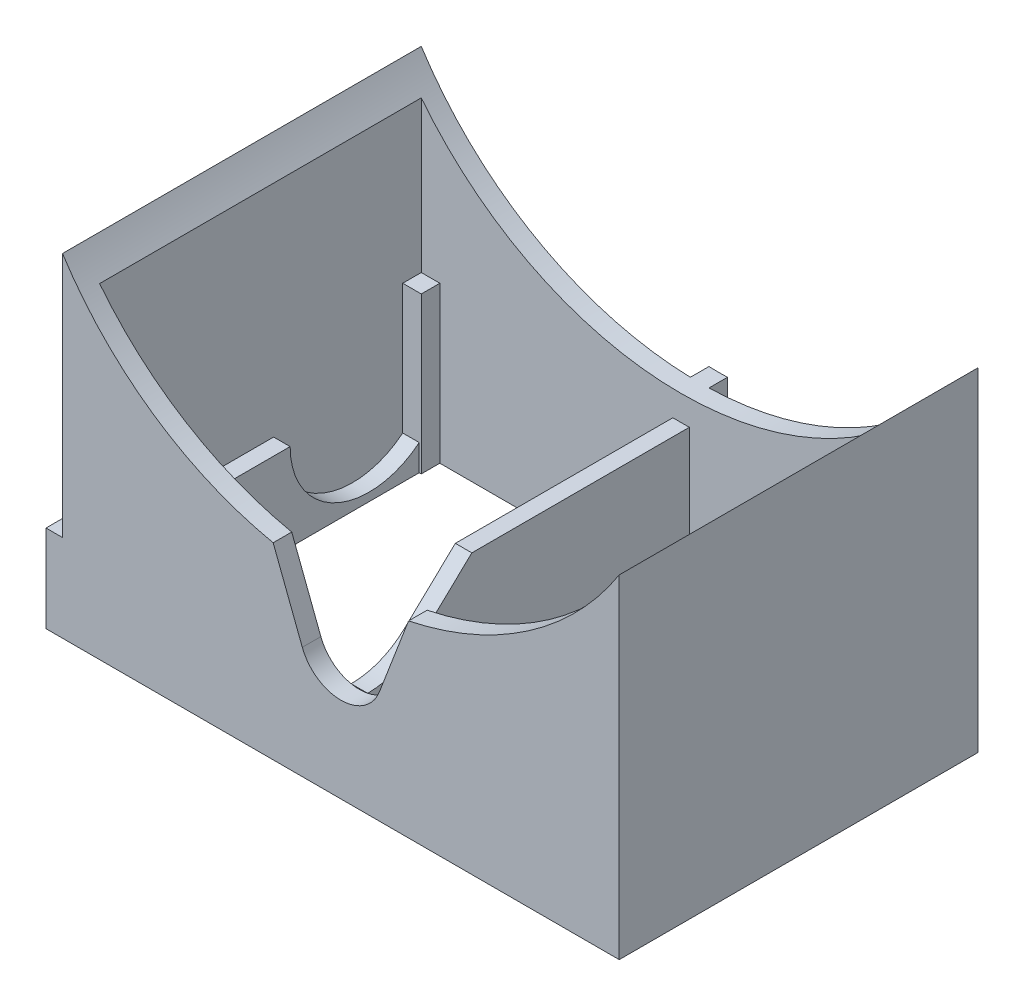
SolidWorks part; units mm, degrees
ref_plane "前视基准面" through (0, 0, 0) normal (0, 0, 1) x (1, 0, 0)
ref_plane "上视基准面" through (0, 0, 0) normal (0, 1, 0) x (1, 0, 0)
ref_plane "右视基准面" through (0, 0, 0) normal (1, 0, 0) x (0, 0, -1)
sketch "草图1" plane through (0, 0, 0) normal (0, 1, 0) x (1, 0, 0)
  line L0 (0, 0) -> (4.5, 0)
  line L1 (4.5, 0) -> (4.5, 4.5)
  line L2 (4.5, 4.5) -> (121.5, 4.5) construction
  line L3 (121.5, 4.5) -> (121.5, 0)
  line L4 (121.5, 0) -> (126, 0)
  line L5 (126, 0) -> (126, -69)
  line L6 (126, -69) -> (121.5, -69)
  line L7 (121.5, -69) -> (121.5, -73.5)
  line L8 (121.5, -73.5) -> (4.5, -73.5) construction
  line L9 (4.5, -73.5) -> (4.5, -69)
  line L10 (4.5, -69) -> (0, -69)
  line L11 (0, -69) -> (0, 0)
  line L12 (4.5, 4.5) -> (61, 4.5)
  line L13 (-4.5, 9) -> (130.5, 9)
  line L14 (-4.5, 9) -> (-4.5, -78)
  line L15 (-4.5, -78) -> (130.5, -78)
  line L16 (130.5, 9) -> (130.5, -78)
  line L17 (61, 4.5) -> (61, -73.5)
  line L18 (61, -73.5) -> (4.5, -73.5)
  line L19 (121.5, 4.5) -> (65, 4.5)
  line L20 (65, 4.5) -> (65, -73.5)
  line L21 (65, -73.5) -> (121.5, -73.5)
  line L22 (61, 4.5) -> (65, 4.5)
  point P17 (63, 4.5)
  point P18 (63, -73.5)
  point P23 (63, 4.5)
  dimension "D1" = 126
  dimension "D2" = 78
  dimension "D3" = 4.5
  dimension "D4" = 4.5
  dimension "D5" = 4.5
  dimension "D6" = 4.5
  dimension "D7" = 4.5
  dimension "D8" = 4.5
  dimension "D9" = 4.5
  dimension "D10" = 4.5
  dimension "D11" = 4
extrude "凸台-拉伸1" add sketch "草图1" along normal blind 37.8
sketch "草图2" plane through (0, 37.8, 0) normal (0, 1, 0) x (1, 0, 0)
  line L0 (4.5, 4.5) -> (61, 4.5) construction
  line L1 (-4.5, 9) -> (130.5, 9)
  line L2 (-4.5, 9) -> (-4.5, -78)
  line L3 (-4.5, -78) -> (130.5, -78)
  line L4 (130.5, 9) -> (130.5, -78)
  line L5 (0, 4.5) -> (126, 4.5)
  line L6 (0, 4.5) -> (0, -73.5)
  line L7 (0, -73.5) -> (126, -73.5)
  line L8 (126, 4.5) -> (126, -73.5)
  line L9 (0, -69) -> (0, 0) construction
  line L10 (61, -73.5) -> (4.5, -73.5) construction
  line L11 (126, 0) -> (126, -69) construction
extrude "凸台-拉伸2" add sketch "草图2" along normal blind 43
sketch "草图3" plane through (0, 0, 78) normal (0, 0, 1) x (1, 0, 0)
  line L0 (63, 80.8) -> (63, 167.3756) construction
  line L1 (-4.5, 80.8) -> (130.5, 80.8) construction
  line L2 (130.5, 80.8) -> (130.5, 0) construction
  line L3 (32.8626, 43.9) -> (91.0379, 43.9) construction
  line L4 (-4.5, 0) -> (130.5, 0) construction
  line L5 (-4.5, 80.8) -> (130.5, 80.8)
  arc A0 (-4.5, 80.8) -> (130.5, 80.8) centre (63, 124.0878) ccw
  dimension "D1" = 43.9
extrude "切除-拉伸1" cut sketch "草图3" against normal through all
sketch "草图4" plane through (0, 0, 78) normal (0, 0, 1) x (1, 0, 0)
  line L0 (63, 43.9) -> (63, 22.4366) construction
  line L1 (53.65, 27.1691) -> (46.585, 45.5981)
  line L2 (46.585, 45.5981) -> (79.415, 45.5981)
  line L3 (79.415, 45.5981) -> (72.35, 27.1691)
  line L4 (57.5225, 20.74) -> (70.5626, 20.74) construction
  line L5 (-4.5, 0) -> (130.5, 0) construction
  arc A0 (-4.5, 80.8) -> (130.5, 80.8) centre (63, 124.0878) ccw construction
  arc A1 (53.65, 27.1691) -> (72.35, 27.1691) centre (63, 30.7535) ccw
  point P0 (63, 43.9)
  dimension "D1" = 20.74
  dimension "D2" = 32.83
  dimension "D3" = 18.7
extrude "切除-拉伸2" cut sketch "草图4" against normal blind 4.5
sketch "草图5" plane through (65, 0, 0) normal (1, 0, 0) x (0, 0, -1)
  line L0 (-73.5, 37.8) -> (-48.24, 37.8)
  line L1 (4.5, 37.8) -> (-73.5, 37.8) construction
  line L2 (-73.5, 37.8) -> (-73.5, 20.9418)
  line L3 (-73.5, 37.8) -> (-73.5, 20.9418) construction
  line L4 (-48.24, 37.8) -> (-60.5637, 26.1034)
  line L5 (-73.5, 20.9418) -> (-73.5, 27.1691) construction
  arc A0 (-73.5, 20.9418) -> (-60.5637, 26.1034) centre (-73.5, 39.7333) ccw
  dimension "D1" = 25.26
  dimension "D2" = 11.6966
extrude "切除-拉伸3" cut sketch "草图5" against normal blind 4.5
sketch "草图6" plane through (0, 0, -9) normal (0, 0, -1) x (-1, 0, 0)
  line L0 (4.5, 0) -> (-130.5, 0) construction
  line L2 (-65.25, 0) -> (-60.75, 0)
  line L3 (-65.25, 0) -> (-65.25, 43.9316)
  line L5 (-60.75, 0) -> (-60.75, 43.9316)
  arc A0 (-65.25, 43.9316) -> (-60.75, 43.9316) centre (-63, 124.0878) ccw
  arc A1 (-130.5, 80.8) -> (4.5, 80.8) centre (-63, 124.0878) ccw construction
  point P6 (-63, 0)
  dimension "D1" = 4.5
extrude "凸台-拉伸3" add sketch "草图6" along normal blind 4.5
sketch "草图7" plane through (-4.5, 0, 0) normal (-1, 0, 0) x (0, 0, 1)
  line L0 (-9, 0) -> (78, 0) construction
  line L1 (-9, 0) -> (12.15, 0)
  line L2 (-9, 0) -> (-9, 21.15)
  line L3 (-9, 21.15) -> (78, 21.15) construction
  line L4 (78, 0) -> (78, 21.15)
  line L5 (43.3, 21.15) -> (78, 21.15)
  line L6 (22.15, 0) -> (78, 0)
  line L7 (78, 80.8) -> (78, 0) construction
  arc A0 (-9, 21.15) -> (12.15, 0) centre (12.15, 21.15) ccw
  arc A1 (43.3, 21.15) -> (22.15, 0) centre (22.15, 21.15) cw
  dimension "D2" = 21.15
  dimension "D3" = 10
extrude "凸台-拉伸4" add sketch "草图7" along normal blind 4
sketch "草图8" plane through (0, 0, 0) normal (1, 0, 0) x (0, 0, -1)
  line L0 (-69, 0) -> (0, 0) construction
  line L2 (0, 37.8) -> (0, 0) construction
  line L4 (0, 6.348) -> (0, 0)
  line L6 (0, 37.8) -> (0, 0) construction
  line L7 (-69, 37.8) -> (-69, 0) construction
  line L8 (-31.3, 0) -> (0, 0)
  line L9 (-31.3, 21.15) -> (-69, 21.15)
  line L10 (-31.3, 21.15) -> (-31.3, 0) construction
  line L11 (-31.3, 0) -> (-69, 0)
  line L12 (-69, 21.15) -> (-69, 0)
  arc A0 (0, 6.348) -> (-31.3, 21.15) centre (-12.15, 21.15) cw
  dimension "D1" = 12.15
  dimension "D3" = 19.15
  dimension "D2" = 21.15
extrude "凸台-拉伸5" add sketch "草图8" along normal blind 4
